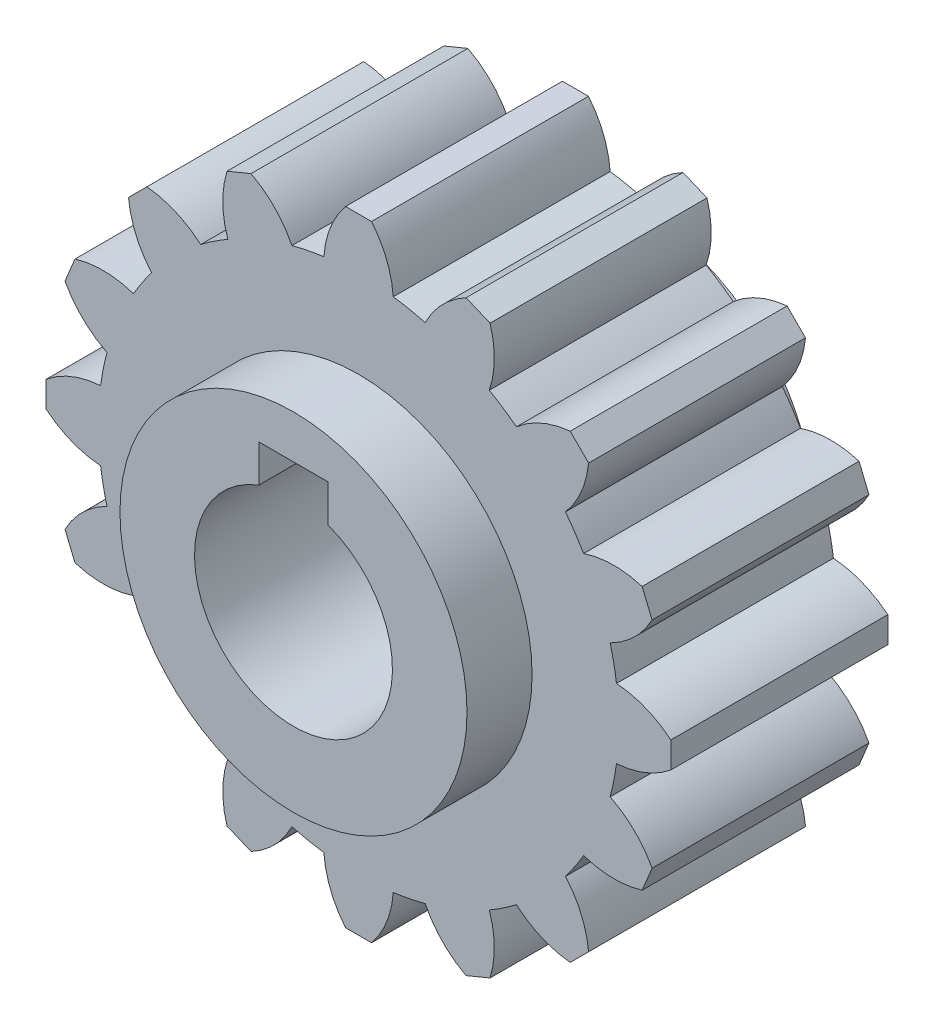
SolidWorks part; units mm, degrees
ref_plane "Front Plane" through (0, 0, 0) normal (0, 0, 1) x (1, 0, 0)
ref_plane "Top Plane" through (0, 0, 0) normal (0, 1, 0) x (1, 0, 0)
ref_plane "Right Plane" through (0, 0, 0) normal (1, 0, 0) x (0, 0, -1)
sketch "Sketch2" plane through (0, 0, 0) normal (0, 0, 1) x (1, 0, 0)
  line L0 (0, 30) -> (0, 36) construction
  line L1 (1.5, 36) -> (-1.5, 36)
  line L2 (8.8591, 30) -> (3.9785, 30) construction
  line L3 (15.1624, 32.6856) -> (12.3908, 33.8337)
  line L4 (26.5165, 24.3952) -> (24.3952, 26.5165)
  line L5 (33.8337, 12.3908) -> (32.6856, 15.1624)
  line L6 (36, -1.5) -> (36, 1.5)
  line L7 (32.6856, -15.1624) -> (33.8337, -12.3908)
  line L8 (24.3952, -26.5165) -> (26.5165, -24.3952)
  line L9 (12.3908, -33.8337) -> (15.1624, -32.6856)
  line L10 (-1.5, -36) -> (1.5, -36)
  line L11 (-15.1624, -32.6856) -> (-12.3908, -33.8337)
  line L12 (-26.5165, -24.3952) -> (-24.3952, -26.5165)
  line L13 (-33.8337, -12.3908) -> (-32.6856, -15.1624)
  line L14 (-36, 1.5) -> (-36, -1.5)
  line L15 (-32.6856, 15.1624) -> (-33.8337, 12.3908)
  line L16 (-24.3952, 26.5165) -> (-26.5165, 24.3952)
  line L17 (-12.3908, 33.8337) -> (-15.1624, 32.6856)
  line L18 (0, 30) -> (-14.7143, 30) construction
  arc A0 (-15.0735, 25.9382) -> (-18.1954, 23.8522) centre (0, 0) ccw
  arc A1 (-1.5, 36) -> (-4, 29.7321) centre (6.9748, 28.9873) ccw
  arc A2 (1.5, 36) -> (4, 29.7321) centre (-6.9748, 28.9873) cw
  arc A3 (12.3908, 33.8337) -> (7.6825, 28.9996) centre (17.5368, 24.1116) ccw
  arc A4 (15.1624, 32.6856) -> (15.0735, 25.9382) centre (4.6491, 29.4499) cw
  arc A5 (24.3952, 26.5165) -> (18.1954, 23.8522) centre (25.429, 15.5652) ccw
  arc A6 (26.5165, 24.3952) -> (23.8522, 18.1954) centre (15.5652, 25.429) cw
  arc A7 (32.6856, 15.1624) -> (25.9382, 15.0735) centre (29.4499, 4.6491) ccw
  arc A8 (33.8337, 12.3908) -> (28.9996, 7.6825) centre (24.1116, 17.5368) cw
  arc A9 (36, 1.5) -> (29.7321, 4) centre (28.9873, -6.9748) ccw
  arc A10 (36, -1.5) -> (29.7321, -4) centre (28.9873, 6.9748) cw
  arc A11 (33.8337, -12.3908) -> (28.9996, -7.6825) centre (24.1116, -17.5368) ccw
  arc A12 (32.6856, -15.1624) -> (25.9382, -15.0735) centre (29.4499, -4.6491) cw
  arc A13 (26.5165, -24.3952) -> (23.8522, -18.1954) centre (15.5652, -25.429) ccw
  arc A14 (24.3952, -26.5165) -> (18.1954, -23.8522) centre (25.429, -15.5652) cw
  arc A15 (15.1624, -32.6856) -> (15.0735, -25.9382) centre (4.6491, -29.4499) ccw
  arc A16 (12.3908, -33.8337) -> (7.6825, -28.9996) centre (17.5368, -24.1116) cw
  arc A17 (1.5, -36) -> (4, -29.7321) centre (-6.9748, -28.9873) ccw
  arc A18 (-1.5, -36) -> (-4, -29.7321) centre (6.9748, -28.9873) cw
  arc A19 (-12.3908, -33.8337) -> (-7.6825, -28.9996) centre (-17.5368, -24.1116) ccw
  arc A20 (-15.1624, -32.6856) -> (-15.0735, -25.9382) centre (-4.6491, -29.4499) cw
  arc A21 (-24.3952, -26.5165) -> (-18.1954, -23.8522) centre (-25.429, -15.5652) ccw
  arc A22 (-26.5165, -24.3952) -> (-23.8522, -18.1954) centre (-15.5652, -25.429) cw
  arc A23 (-32.6856, -15.1624) -> (-25.9382, -15.0735) centre (-29.4499, -4.6491) ccw
  arc A24 (-33.8337, -12.3908) -> (-28.9996, -7.6825) centre (-24.1116, -17.5368) cw
  arc A25 (-36, -1.5) -> (-29.7321, -4) centre (-28.9873, 6.9748) ccw
  arc A26 (-36, 1.5) -> (-29.7321, 4) centre (-28.9873, -6.9748) cw
  arc A27 (-33.8337, 12.3908) -> (-28.9996, 7.6825) centre (-24.1116, 17.5368) ccw
  arc A28 (-32.6856, 15.1624) -> (-25.9382, 15.0735) centre (-29.4499, 4.6491) cw
  arc A29 (-26.5165, 24.3952) -> (-23.8522, 18.1954) centre (-15.5652, 25.429) ccw
  arc A30 (-24.3952, 26.5165) -> (-18.1954, 23.8522) centre (-25.429, 15.5652) cw
  arc A31 (-15.1624, 32.6856) -> (-15.0735, 25.9382) centre (-4.6491, 29.4499) ccw
  arc A32 (-12.3908, 33.8337) -> (-7.6825, 28.9996) centre (-17.5368, 24.1116) cw
  arc A33 (-23.8522, 18.1954) -> (-25.9382, 15.0735) centre (0, 0) ccw
  arc A34 (-28.9996, 7.6825) -> (-29.7321, 4) centre (0, 0) ccw
  arc A35 (-29.7321, -4) -> (-28.9996, -7.6825) centre (0, 0) ccw
  arc A36 (-25.9382, -15.0735) -> (-15.0735, -25.9382) centre (0, 0) ccw
  arc A37 (-7.6825, -28.9996) -> (-4, -29.7321) centre (0, 0) ccw
  arc A38 (4, -29.7321) -> (7.6825, -28.9996) centre (0, 0) ccw
  arc A39 (15.0735, -25.9382) -> (18.1954, -23.8522) centre (0, 0) ccw
  arc A40 (23.8522, -18.1954) -> (25.9382, -15.0735) centre (0, 0) ccw
  arc A41 (28.9996, -7.6825) -> (29.7321, -4) centre (0, 0) ccw
  arc A42 (29.7321, 4) -> (28.9996, 7.6825) centre (0, 0) ccw
  arc A43 (25.9382, 15.0735) -> (23.8522, 18.1954) centre (0, 0) ccw
  arc A44 (18.1954, 23.8522) -> (15.0735, 25.9382) centre (0, 0) ccw
  arc A45 (7.6825, 28.9996) -> (4, 29.7321) centre (0, 0) ccw
  arc A46 (-4, 29.7321) -> (-7.6825, 28.9996) centre (0, 0) ccw
  dimension "D1" = 60
  dimension "D2" = 6
  dimension "D4" = 11
  dimension "D3" = 3
  dimension "D5" = 8
  dimension "D6" = 16
extrude "Boss-Extrude1" add sketch "Sketch2" along normal mid plane 25 contours A1 A46 A32 L17 A31 A0 A30 L16 A29 A33 A28 L15 A27 A34 A26 L14 A25 A35 A24 L13 A23 A36 A20 L11 A19 A37 A18 L10 A17 A38 A16 L9 A15 A39 A14 L8 A13 A40 A12 L7 A11 A41 A10 L6 A9 A42 A8 L5 A7
sketch "Sketch3" plane through (0, 0, 0) normal (0, 0, 1) x (1, 0, 0)
  circle A0 centre (0, 0) radius 20
  dimension "D1" = 40
extrude "Boss-Extrude2" add sketch "Sketch3" along normal mid plane 40
sketch "Sketch4" plane through (0, 0, 20) normal (0, 0, 1) x (1, 0, 0)
  line L0 (0, 0) -> (0, 15) construction
  line L1 (4, 15) -> (4, 10.6834)
  line L2 (4, 15) -> (-4, 15)
  line L3 (-4, 15) -> (-4, 10.6834)
  arc A0 (-4, 10.6834) -> (4, 10.6834) centre (0, 0) ccw
  dimension "D1" = 15
  dimension "D2" = 8
extrude "Cut-Extrude1" cut sketch "Sketch4" against normal through all both and the other way through all
